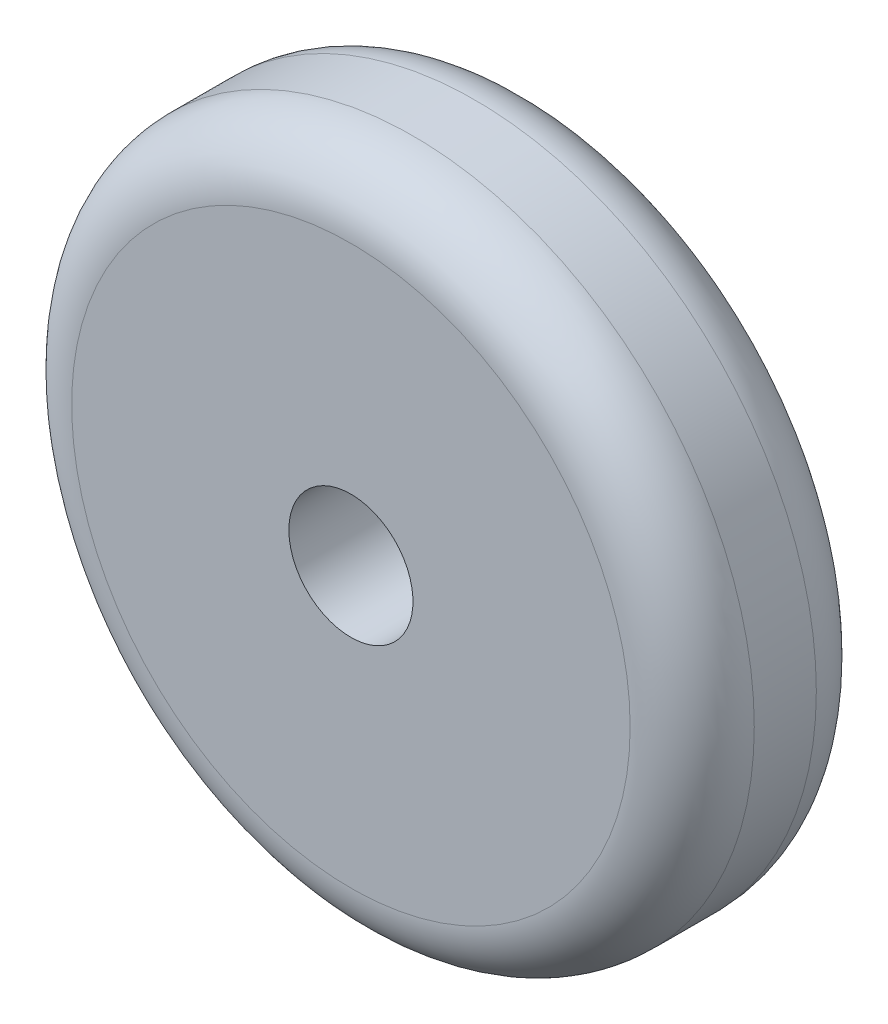
SolidWorks part; units mm, degrees
material "Rubber"
ref_plane "Front Plane" through (0, 0, 0) normal (0, 0, 1) x (1, 0, 0)
ref_plane "Top Plane" through (0, 0, 0) normal (0, 1, 0) x (1, 0, 0)
ref_plane "Right Plane" through (0, 0, 0) normal (1, 0, 0) x (0, 0, -1)
sketch "Sketch2" plane through (0, 0, 0) normal (0, 0, 1) x (1, 0, 0)
  circle A0 centre (0, 0) radius 13.97
  circle A1 centre (0, 0) radius 2.54
  dimension "D1" = 27.94
extrude "Boss-Extrude1" add sketch "Sketch2" along normal blind 7.62
fillet "Fillet1" radius 2.54 2 edges at (13.97, 0, 0) (13.97, 0, 7.62)
